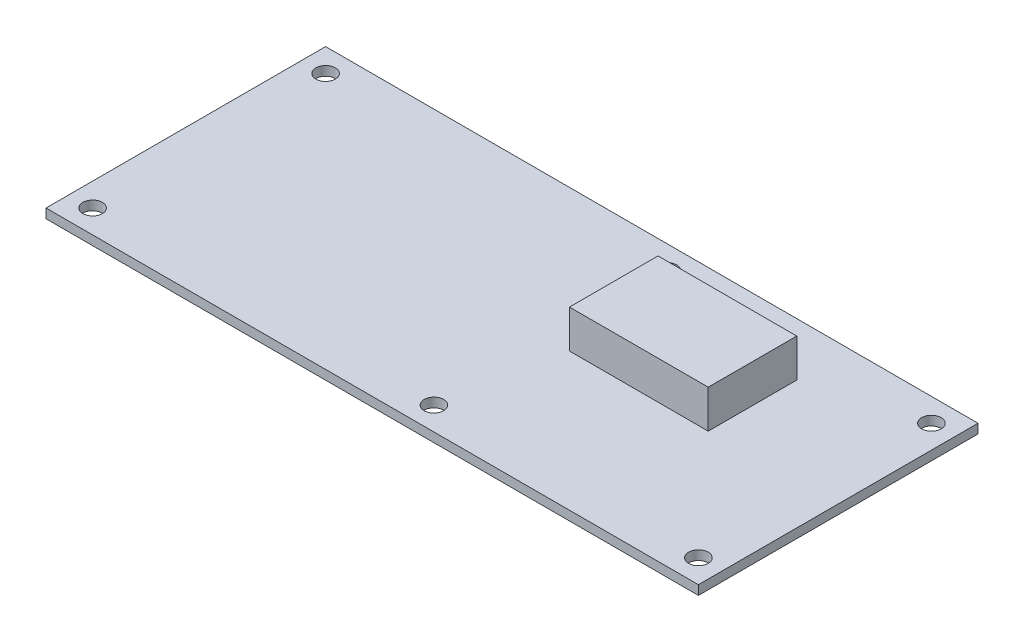
SolidWorks part; units mm, degrees
ref_plane "Front Plane" through (0, 0, 0) normal (0, 0, 1) x (1, 0, 0)
ref_plane "Top Plane" through (0, 0, 0) normal (0, 1, 0) x (1, 0, 0)
ref_plane "Right Plane" through (0, 0, 0) normal (1, 0, 0) x (0, 0, -1)
sketch "Sketch1" plane through (0, 0, 0) normal (0, 1, 0) x (1, 0, 0)
  line L0 (-73.25, 30) -> (-73.25, 25)
  line L1 (-78.25, 30) -> (61.75, 30)
  line L2 (-78.25, 30) -> (-78.25, -30)
  line L3 (-78.25, -30) -> (61.75, -30)
  line L4 (61.75, 30) -> (61.75, -30)
  line L5 (-73.25, 25) -> (-78.25, 25)
  line L6 (-78.25, -25) -> (-73.25, -25)
  line L7 (-73.25, -25) -> (-73.25, -30)
  line L8 (0, 30) -> (0, -30)
  line L9 (-73.25, 25) -> (61.75, 25)
  line L10 (-73.25, -25) -> (61.75, -25)
  line L11 (56.75, 30) -> (56.75, -30)
  line L12 (61.75, 0) -> (54.75, 0)
  line L13 (61.75, 10) -> (54.75, 10)
  line L14 (54.75, 10) -> (54.75, -10)
  line L15 (54.75, -10) -> (61.75, -10)
  line L17 (4.5, 20) -> (29.5, 20)
  line L18 (4.5, 20) -> (4.5, 5)
  line L19 (4.5, 5) -> (29.5, 5)
  line L20 (29.5, 20) -> (29.5, 5)
  line L21 (-58.5469, 30) -> (-51.5469, 30)
  line L22 (-58.5469, 30) -> (-58.5469, 22)
  line L23 (-58.5469, 22) -> (-51.5469, 22)
  line L24 (-51.5469, 30) -> (-51.5469, 22)
  line L25 (-49.5469, 30) -> (-42.5469, 30)
  line L26 (-49.5469, 30) -> (-49.5469, 22)
  line L27 (-49.5469, 22) -> (-42.5469, 22)
  line L28 (-42.5469, 30) -> (-42.5469, 22)
  circle A0 centre (-73.25, 25) radius 2.0955
  circle A1 centre (-73.25, -25) radius 2.0955
  circle A2 centre (0, 25) radius 2.0955
  circle A3 centre (0, -25) radius 2.0955
  circle A4 centre (56.75, 25) radius 2.0955
  circle A5 centre (56.75, -25) radius 2.0955
  point P19 (0, 25)
  point P20 (0, -25)
  point P21 (56.75, 25)
  point P22 (56.75, -25)
  point P35 (54.75, 0)
  dimension "D9" = 7
  dimension "D19" = 4.191
  dimension "D1" = 60
  dimension "D2" = 140
  dimension "D3" = 5
  dimension "D4" = 5
  dimension "D5" = 5
  dimension "D6" = 5
  dimension "D7" = 78.25
  dimension "D8" = 5
  dimension "D10" = 20
  dimension "D11" = 25
  dimension "D12" = 15
  dimension "D13" = 4.5
  dimension "D14" = 10
  dimension "D15" = 7
  dimension "D16" = 7
  dimension "D17" = 2
  dimension "D18" = 8
extrude "Boss-Extrude1" add sketch "Sketch1" along normal blind 2 contours A3 L8 A2 L9 L28 L27 L26 L24 L23 L22 A0 L5 L2 L6 A1 L10 | A5 L11 L15 L14 L13 A4 L9 A2 L8 A3 L10 L17 L20 L19 L18 | A3 L10 A1 L7 L3 L8 | A5 L10 A3 L8 L3 L11 | A5 L11 L3 L4 L10 | A5 L10 L4 L15 L11 | A4 L11 L13 L4 L9 | A4 L9 L4 L1 L11 | A4 L11 L1 L8 A2 L9 | A1 L6 L2 L3 L7 | A0 L0 L1 L2 L5 | A0 L9 L22 L1 L0 | A2 L8 L1 L28 L9 | L11 L15 L4 L12 | L14 L15 L11 L12 | L4 L13 L11 L12 | L13 L14 L12 L11 | L20 L17 L18 L19 | L28 L9 L26 L27 | L26 L1 L24 L9 | L24 L9 L22 L23 | L24 L1 L22 L9 | L28 L1 L26 L9
sketch "Sketch2" plane through (0, 2, 0) normal (0, 1, 0) x (1, 0, 0)
  line L1 (4.4982, -0.4148) -> (34.2753, -0.4148)
  line L2 (4.4982, -0.4148) -> (4.4982, 18.5854)
  line L3 (4.4982, 18.5854) -> (34.2753, 18.5854)
  line L4 (34.2753, -0.4148) -> (34.2753, 18.5854)
extrude "Boss-Extrude2" add sketch "Sketch2" along normal blind 8.174
